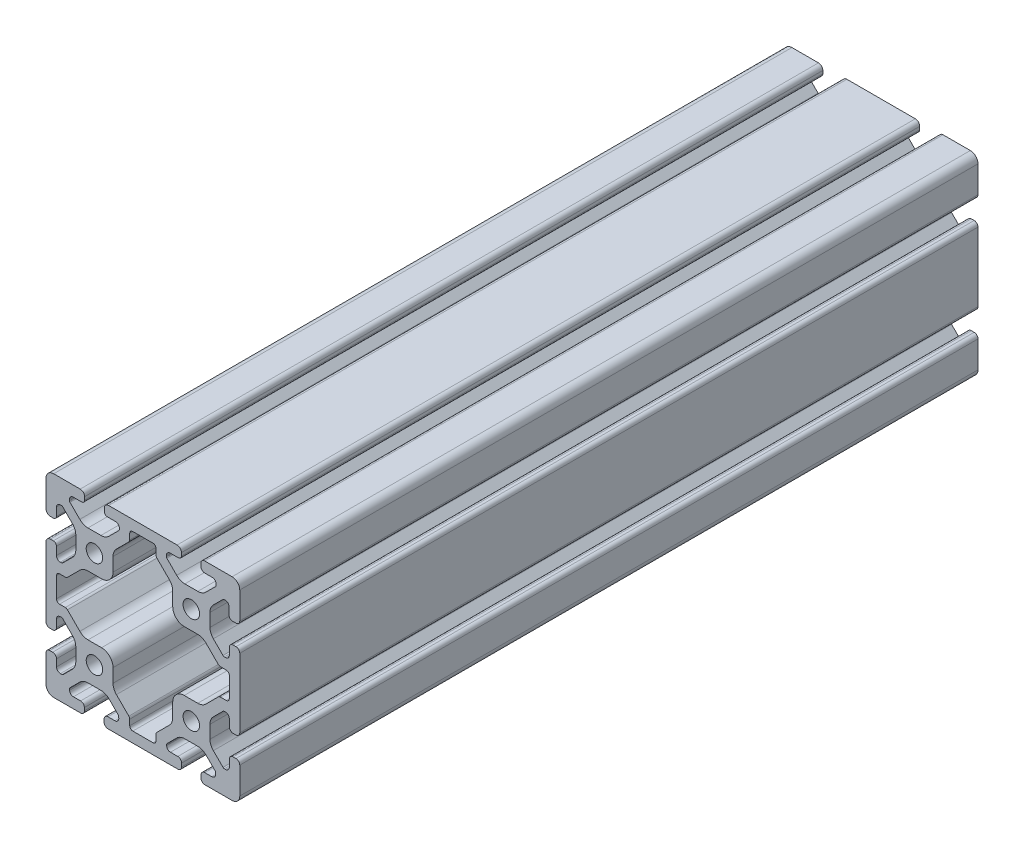
SolidWorks part; units mm, degrees
material "6061 Alloy"
ref_plane "Front Plane" through (0, 0, 0) normal (0, 0, 1) x (1, 0, 0)
ref_plane "Top Plane" through (0, 0, 0) normal (0, 1, 0) x (1, 0, 0)
ref_plane "Right Plane" through (0, 0, 0) normal (1, 0, 0) x (0, 0, -1)
sketch "Sketch1" plane through (0, 0, 0) normal (0, 0, 1) x (1, 0, 0)
  line L0 (0, -40) -> (0, 40) construction
  line L1 (0, 0) -> (-43.5804, 43.5804) construction
  line L2 (-20, 20) -> (-47.7323, 20) construction
  line L3 (-20, 20) -> (3.796, 43.796) construction
  line L4 (-20, 20) -> (-20, 43.5758) construction
  line L5 (-20, -27.7) -> (-20, -47.5576) construction
  line L131 (29.0912, 26.0365) -> (33.0827, 30.028)
  line L132 (27.7, 17.3222) -> (27.7, 22.6778)
  line L133 (29.0912, 13.9635) -> (33.0827, 9.972)
  line L134 (33.6201, 9.7494) -> (34.11, 9.7494)
  line L135 (35.68, 11.3194) -> (35.68, 14.2221)
  line L136 (37.25, 15.7921) -> (38.43, 15.7921)
  line L137 (40, 14.2221) -> (40, 7.0214)
  line L138 (40, 7.0214) -> (40, -7.0214)
  line L139 (40, -7.0214) -> (40, -14.2221)
  line L140 (38.43, -15.7921) -> (37.25, -15.7921)
  line L141 (35.68, -14.2221) -> (35.68, -11.3194)
  line L142 (33.6201, -9.7494) -> (34.11, -9.7494)
  line L143 (29.0912, -13.9635) -> (33.0827, -9.972)
  line L144 (27.7, -22.6778) -> (27.7, -17.3222)
  line L145 (29.0912, -26.0365) -> (33.0827, -30.028)
  line L146 (33.6201, -30.2506) -> (34.11, -30.2506)
  line L147 (35.68, -28.6806) -> (35.68, -25.7779)
  line L148 (37.25, -24.2079) -> (38.43, -24.2079)
  line L149 (40, -25.7779) -> (40, -33.0259)
  line L150 (40, -33.0259) -> (40, -36.83)
  line L151 (36.83, -40) -> (32.9998, -40)
  line L152 (32.9998, -40) -> (25.5696, -40)
  line L153 (23.9996, -38.43) -> (23.9996, -37.25)
  line L154 (25.5696, -35.68) -> (28.4723, -35.68)
  line L155 (30.0413, -34.0552) -> (30.0171, -33.3605)
  line L156 (29.7949, -32.8496) -> (26.0365, -29.0912)
  line L157 (17.3222, -27.7) -> (22.6778, -27.7)
  line L158 (10.035, -33.0197) -> (13.9635, -29.0912)
  line L159 (9.8124, -33.8926) -> (9.8124, -33.5571)
  line L160 (11.3824, -35.4626) -> (14.4246, -35.4626)
  line L161 (15.9946, -37.0326) -> (15.9946, -38.43)
  line L162 (14.4246, -40) -> (6.9987, -40)
  line L163 (6.9987, -40) -> (-6.9987, -40)
  line L164 (-6.9987, -40) -> (-14.4292, -40)
  line L165 (-15.9992, -38.43) -> (-15.9992, -37.25)
  line L166 (-14.4292, -35.68) -> (-11.5265, -35.68)
  line L167 (-9.9574, -34.0552) -> (-9.9816, -33.3618)
  line L168 (-10.2038, -32.8509) -> (-13.9635, -29.0912)
  line L169 (-22.6778, -27.7) -> (-17.3222, -27.7)
  line L170 (-30.028, -33.0827) -> (-26.0365, -29.0912)
  line L171 (-30.2506, -34.11) -> (-30.2506, -33.6201)
  line L172 (-28.6806, -35.68) -> (-25.7231, -35.68)
  line L173 (-24.1531, -37.25) -> (-24.1531, -38.43)
  line L174 (-25.7231, -40) -> (-33, -40)
  line L175 (-33, -40) -> (-36.83, -40)
  line L176 (-40, -36.83) -> (-40, -33.0191)
  line L177 (-40, -33.0191) -> (-40, -25.591)
  line L178 (-38.43, -24.021) -> (-37.25, -24.021)
  line L179 (-35.68, -28.4937) -> (-35.68, -25.591)
  line L180 (-34.0552, -30.0627) -> (-33.3827, -30.0392)
  line L181 (-32.8718, -29.8171) -> (-29.0912, -26.0365)
  line L182 (-27.7, -22.6778) -> (-27.7, -17.3222)
  line L183 (-29.0912, -13.9635) -> (-33.0827, -9.972)
  line L184 (-34.11, -9.7494) -> (-33.6201, -9.7494)
  line L185 (-35.68, -11.3194) -> (-35.68, -14.4473)
  line L186 (-38.43, -16.0173) -> (-37.25, -16.0173)
  line L187 (-40, -14.4473) -> (-40, -7.0169)
  line L188 (-40, -7.0169) -> (-40, 7.0169)
  line L189 (-40, 7.0169) -> (-40, 14.1348)
  line L190 (-38.1948, 15.94) -> (-36.9772, 15.94)
  line L191 (-35.68, 11.3194) -> (-35.68, 14.6428)
  line L192 (-34.11, 9.7494) -> (-33.6201, 9.7494)
  line L193 (-33.0827, 9.972) -> (-29.0912, 13.9635)
  line L194 (-27.7, 17.3222) -> (-27.7, 22.6778)
  line L195 (-29.0912, 26.0365) -> (-33.0827, 30.028)
  line L196 (-34.11, 30.2506) -> (-33.6201, 30.2506)
  line L197 (-35.68, 28.6806) -> (-35.68, 25.3572)
  line L198 (-38.1948, 24.06) -> (-36.9772, 24.06)
  line L199 (-40, 25.8652) -> (-40, 33.3181)
  line L200 (-40, 33.3181) -> (-40, 36.83)
  line L201 (-36.83, 40) -> (-33.0314, 40)
  line L202 (-33.0314, 40) -> (-25.8652, 40)
  line L203 (-24.06, 36.9772) -> (-24.06, 38.1948)
  line L204 (-25.3572, 35.68) -> (-28.7018, 35.68)
  line L205 (-30.285, 33.6069) -> (-30.285, 34.0968)
  line L206 (-30.0961, 33.1508) -> (-26.0365, 29.0912)
  line L207 (-22.6778, 27.7) -> (-17.3222, 27.7)
  line L208 (-13.9635, 29.0912) -> (-9.9039, 33.1508)
  line L209 (-9.715, 33.6069) -> (-9.715, 34.0968)
  line L210 (-14.6428, 35.68) -> (-11.2982, 35.68)
  line L211 (-15.94, 36.9772) -> (-15.94, 38.1948)
  line L212 (-14.1348, 40) -> (-6.9844, 40)
  line L213 (-6.9844, 40) -> (6.9844, 40)
  line L214 (6.9844, 40) -> (14.1348, 40)
  line L215 (15.94, 36.9772) -> (15.94, 38.1948)
  line L216 (14.6428, 35.68) -> (11.2982, 35.68)
  line L217 (9.715, 33.6069) -> (9.715, 34.0968)
  line L218 (9.9039, 33.1508) -> (13.9635, 29.0912)
  line L219 (17.3222, 27.7) -> (22.6778, 27.7)
  line L220 (26.0365, 29.0912) -> (30.028, 33.0827)
  line L221 (30.2506, 33.6201) -> (30.2506, 34.11)
  line L222 (25.5409, 35.679) -> (28.6258, 35.679)
  line L223 (23.9709, 37.249) -> (23.9709, 38.43)
  line L224 (25.5409, 40) -> (36.83, 40)
  line L226 (40, 36.83) -> (40, 32.9339)
  line L227 (40, 32.9339) -> (40, 25.7779)
  line L228 (38.43, 24.2079) -> (37.0956, 24.2079)
  line L229 (35.5256, 25.7779) -> (35.5256, 28.6806)
  line L230 (33.6201, 30.2506) -> (33.9556, 30.2506)
  line L231 (17.07, 12.32) -> (22.6578, 12.32)
  line L232 (26.0165, 10.9288) -> (31.1439, 5.8014)
  line L233 (32.0419, 5.4294) -> (34.41, 5.4294)
  line L234 (35.68, -4.1594) -> (35.68, 4.1594)
  line L235 (32.0419, -5.4294) -> (34.41, -5.4294)
  line L236 (26.0165, -10.9288) -> (31.1439, -5.8014)
  line L237 (17.07, -12.32) -> (22.6578, -12.32)
  line L238 (12.32, -22.6578) -> (12.32, -17.07)
  line L239 (5.8014, -31.1439) -> (10.9288, -26.0165)
  line L240 (5.4294, -34.41) -> (5.4294, -32.0419)
  line L241 (-4.1594, -35.68) -> (4.1594, -35.68)
  line L242 (-5.4294, -34.41) -> (-5.4294, -32.0419)
  line L243 (-5.8014, -31.1439) -> (-10.9288, -26.0165)
  line L244 (-12.32, -22.6578) -> (-12.32, -17.07)
  line L245 (-22.6578, -12.32) -> (-17.07, -12.32)
  line L246 (-26.0165, -10.9288) -> (-31.1439, -5.8014)
  line L247 (-34.41, -5.4294) -> (-32.0419, -5.4294)
  line L248 (-35.68, -4.1594) -> (-35.68, 4.1594)
  line L249 (-34.41, 5.4294) -> (-32.0419, 5.4294)
  line L250 (-31.1439, 5.8014) -> (-26.0165, 10.9288)
  line L251 (-22.6578, 12.32) -> (-17.07, 12.32)
  line L252 (-12.32, 17.07) -> (-12.32, 22.6578)
  line L253 (-10.9288, 26.0165) -> (-5.8014, 31.1439)
  line L254 (-5.4294, 32.0419) -> (-5.4294, 34.41)
  line L255 (-4.1594, 35.68) -> (4.1594, 35.68)
  line L256 (5.4294, 32.0419) -> (5.4294, 34.41)
  line L257 (5.8014, 31.1439) -> (10.9288, 26.0165)
  line L258 (12.32, 17.07) -> (12.32, 22.6578)
  line L260 (-40, 0) -> (40, 0) construction
  circle A116 centre (-20, 20) radius 3.4
  circle A117 centre (20, 20) radius 3.4
  circle A118 centre (20, -20) radius 3.4
  circle A119 centre (-20, -20) radius 3.4
  arc A120 (29.0912, 26.0365) -> (27.7, 22.6778) centre (32.45, 22.6778) ccw
  arc A121 (27.7, 17.3222) -> (29.0912, 13.9635) centre (32.45, 17.3222) ccw
  arc A122 (33.0827, 9.972) -> (33.6201, 9.7494) centre (33.6201, 10.5094) ccw
  arc A123 (34.11, 9.7494) -> (35.68, 11.3194) centre (34.11, 11.3194) ccw
  arc A124 (37.25, 15.7921) -> (35.68, 14.2221) centre (37.25, 14.2221) ccw
  arc A125 (40, 14.2221) -> (38.43, 15.7921) centre (38.43, 14.2221) ccw
  arc A126 (38.43, -15.7921) -> (40, -14.2221) centre (38.43, -14.2221) ccw
  arc A127 (35.68, -14.2221) -> (37.25, -15.7921) centre (37.25, -14.2221) ccw
  arc A128 (35.68, -11.3194) -> (34.11, -9.7494) centre (34.11, -11.3194) ccw
  arc A129 (33.6201, -9.7494) -> (33.0827, -9.972) centre (33.6201, -10.5094) ccw
  arc A130 (29.0912, -13.9635) -> (27.7, -17.3222) centre (32.45, -17.3222) ccw
  arc A131 (27.7, -22.6778) -> (29.0912, -26.0365) centre (32.45, -22.6778) ccw
  arc A132 (33.0827, -30.028) -> (33.6201, -30.2506) centre (33.6201, -29.4906) ccw
  arc A133 (34.11, -30.2506) -> (35.68, -28.6806) centre (34.11, -28.6806) ccw
  arc A134 (37.25, -24.2079) -> (35.68, -25.7779) centre (37.25, -25.7779) ccw
  arc A135 (40, -25.7779) -> (38.43, -24.2079) centre (38.43, -25.7779) ccw
  arc A136 (36.83, -40) -> (40, -36.83) centre (36.83, -36.83) ccw
  arc A137 (23.9996, -38.43) -> (25.5696, -40) centre (25.5696, -38.43) ccw
  arc A138 (25.5696, -35.68) -> (23.9996, -37.25) centre (25.5696, -37.25) ccw
  arc A139 (28.4723, -35.68) -> (30.0413, -34.0552) centre (28.4723, -34.11) ccw
  arc A140 (30.0171, -33.3605) -> (29.7949, -32.8496) centre (29.2575, -33.387) ccw
  arc A141 (26.0365, -29.0912) -> (22.6778, -27.7) centre (22.6778, -32.45) ccw
  arc A142 (17.3222, -27.7) -> (13.9635, -29.0912) centre (17.3222, -32.45) ccw
  arc A143 (10.035, -33.0197) -> (9.8124, -33.5571) centre (10.5724, -33.5571) ccw
  arc A144 (9.8124, -33.8926) -> (11.3824, -35.4626) centre (11.3824, -33.8926) ccw
  arc A145 (15.9946, -37.0326) -> (14.4246, -35.4626) centre (14.4246, -37.0326) ccw
  arc A146 (14.4246, -40) -> (15.9946, -38.43) centre (14.4246, -38.43) ccw
  arc A147 (-15.9992, -38.43) -> (-14.4292, -40) centre (-14.4292, -38.43) ccw
  arc A148 (-14.4292, -35.68) -> (-15.9992, -37.25) centre (-14.4292, -37.25) ccw
  arc A149 (-11.5265, -35.68) -> (-9.9574, -34.0552) centre (-11.5265, -34.11) ccw
  arc A150 (-9.9816, -33.3618) -> (-10.2038, -32.8509) centre (-10.7412, -33.3883) ccw
  arc A151 (-13.9635, -29.0912) -> (-17.3222, -27.7) centre (-17.3222, -32.45) ccw
  arc A152 (-22.6778, -27.7) -> (-26.0365, -29.0912) centre (-22.6778, -32.45) ccw
  arc A153 (-30.028, -33.0827) -> (-30.2506, -33.6201) centre (-29.4906, -33.6201) ccw
  arc A154 (-30.2506, -34.11) -> (-28.6806, -35.68) centre (-28.6806, -34.11) ccw
  arc A155 (-24.1531, -37.25) -> (-25.7231, -35.68) centre (-25.7231, -37.25) ccw
  arc A156 (-25.7231, -40) -> (-24.1531, -38.43) centre (-25.7231, -38.43) ccw
  arc A157 (-40, -36.83) -> (-36.83, -40) centre (-36.83, -36.83) ccw
  arc A158 (-38.43, -24.021) -> (-40, -25.591) centre (-38.43, -25.591) ccw
  arc A159 (-35.68, -25.591) -> (-37.25, -24.021) centre (-37.25, -25.591) ccw
  arc A160 (-35.68, -28.4937) -> (-34.0552, -30.0627) centre (-34.11, -28.4937) ccw
  arc A161 (-33.3827, -30.0392) -> (-32.8718, -29.8171) centre (-33.4092, -29.2797) ccw
  arc A162 (-29.0912, -26.0365) -> (-27.7, -22.6778) centre (-32.45, -22.6778) ccw
  arc A163 (-27.7, -17.3222) -> (-29.0912, -13.9635) centre (-32.45, -17.3222) ccw
  arc A164 (-33.0827, -9.972) -> (-33.6201, -9.7494) centre (-33.6201, -10.5094) ccw
  arc A165 (-34.11, -9.7494) -> (-35.68, -11.3194) centre (-34.11, -11.3194) ccw
  arc A166 (-37.25, -16.0173) -> (-35.68, -14.4473) centre (-37.25, -14.4473) ccw
  arc A167 (-40, -14.4473) -> (-38.43, -16.0173) centre (-38.43, -14.4473) ccw
  arc A168 (-38.1948, 15.94) -> (-40, 14.1348) centre (-38.1948, 14.1348) ccw
  arc A169 (-35.68, 14.6428) -> (-36.9772, 15.94) centre (-36.9772, 14.6428) ccw
  arc A170 (-35.68, 11.3194) -> (-34.11, 9.7494) centre (-34.11, 11.3194) ccw
  arc A171 (-33.6201, 9.7494) -> (-33.0827, 9.972) centre (-33.6201, 10.5094) ccw
  arc A172 (-29.0912, 13.9635) -> (-27.7, 17.3222) centre (-32.45, 17.3222) ccw
  arc A173 (-27.7, 22.6778) -> (-29.0912, 26.0365) centre (-32.45, 22.6778) ccw
  arc A174 (-33.0827, 30.028) -> (-33.6201, 30.2506) centre (-33.6201, 29.4906) ccw
  arc A175 (-34.11, 30.2506) -> (-35.68, 28.6806) centre (-34.11, 28.6806) ccw
  arc A176 (-36.9772, 24.06) -> (-35.68, 25.3572) centre (-36.9772, 25.3572) ccw
  arc A177 (-40, 25.8652) -> (-38.1948, 24.06) centre (-38.1948, 25.8652) ccw
  arc A178 (-36.83, 40) -> (-40, 36.83) centre (-36.83, 36.83) ccw
  arc A179 (-24.06, 38.1948) -> (-25.8652, 40) centre (-25.8652, 38.1948) ccw
  arc A180 (-25.3572, 35.68) -> (-24.06, 36.9772) centre (-25.3572, 36.9772) ccw
  arc A181 (-28.7018, 35.68) -> (-30.285, 34.0968) centre (-28.7018, 34.0968) ccw
  arc A182 (-30.285, 33.6069) -> (-30.0961, 33.1508) centre (-29.6399, 33.6069) ccw
  arc A183 (-26.0365, 29.0912) -> (-22.6778, 27.7) centre (-22.6778, 32.45) ccw
  arc A184 (-17.3222, 27.7) -> (-13.9635, 29.0912) centre (-17.3222, 32.45) ccw
  arc A185 (-9.9039, 33.1508) -> (-9.715, 33.6069) centre (-10.3601, 33.6069) ccw
  arc A186 (-9.715, 34.0968) -> (-11.2982, 35.68) centre (-11.2982, 34.0968) ccw
  arc A187 (-15.94, 36.9772) -> (-14.6428, 35.68) centre (-14.6428, 36.9772) ccw
  arc A188 (-14.1348, 40) -> (-15.94, 38.1948) centre (-14.1348, 38.1948) ccw
  arc A189 (15.94, 38.1948) -> (14.1348, 40) centre (14.1348, 38.1948) ccw
  arc A190 (14.6428, 35.68) -> (15.94, 36.9772) centre (14.6428, 36.9772) ccw
  arc A191 (11.2982, 35.68) -> (9.715, 34.0968) centre (11.2982, 34.0968) ccw
  arc A192 (9.715, 33.6069) -> (9.9039, 33.1508) centre (10.3601, 33.6069) ccw
  arc A193 (13.9635, 29.0912) -> (17.3222, 27.7) centre (17.3222, 32.45) ccw
  arc A194 (22.6778, 27.7) -> (26.0365, 29.0912) centre (22.6778, 32.45) ccw
  arc A195 (30.028, 33.0827) -> (30.2506, 33.6201) centre (29.4906, 33.6201) ccw
  arc A196 (30.2506, 34.11) -> (28.6258, 35.679) centre (28.6806, 34.11) ccw
  arc A197 (23.9709, 37.249) -> (25.5409, 35.679) centre (25.5409, 37.249) ccw
  arc A198 (25.5409, 40) -> (23.9709, 38.43) centre (25.5409, 38.43) ccw
  arc A199 (40, 36.83) -> (36.83, 40) centre (36.83, 36.83) ccw
  arc A200 (38.43, 24.2079) -> (40, 25.7779) centre (38.43, 25.7779) ccw
  arc A201 (35.5256, 25.7779) -> (37.0956, 24.2079) centre (37.0956, 25.7779) ccw
  arc A202 (35.5256, 28.6806) -> (33.9556, 30.2506) centre (33.9556, 28.6806) ccw
  arc A203 (33.6201, 30.2506) -> (33.0827, 30.028) centre (33.6201, 29.4906) ccw
  arc A204 (26.0165, 10.9288) -> (22.6578, 12.32) centre (22.6578, 7.57) ccw
  arc A205 (31.1439, 5.8014) -> (32.0419, 5.4294) centre (32.0419, 6.6994) ccw
  arc A206 (35.68, 4.1594) -> (34.41, 5.4294) centre (34.41, 4.1594) ccw
  arc A207 (34.41, -5.4294) -> (35.68, -4.1594) centre (34.41, -4.1594) ccw
  arc A208 (32.0419, -5.4294) -> (31.1439, -5.8014) centre (32.0419, -6.6994) ccw
  arc A209 (22.6578, -12.32) -> (26.0165, -10.9288) centre (22.6578, -7.57) ccw
  arc A210 (17.07, -12.32) -> (12.32, -17.07) centre (17.07, -17.07) ccw
  arc A211 (10.9288, -26.0165) -> (12.32, -22.6578) centre (7.57, -22.6578) ccw
  arc A212 (5.8014, -31.1439) -> (5.4294, -32.0419) centre (6.6994, -32.0419) ccw
  arc A213 (4.1594, -35.68) -> (5.4294, -34.41) centre (4.1594, -34.41) ccw
  arc A214 (-5.4294, -34.41) -> (-4.1594, -35.68) centre (-4.1594, -34.41) ccw
  arc A215 (-5.4294, -32.0419) -> (-5.8014, -31.1439) centre (-6.6994, -32.0419) ccw
  arc A216 (-12.32, -22.6578) -> (-10.9288, -26.0165) centre (-7.57, -22.6578) ccw
  arc A217 (-12.32, -17.07) -> (-17.07, -12.32) centre (-17.07, -17.07) ccw
  arc A218 (-26.0165, -10.9288) -> (-22.6578, -12.32) centre (-22.6578, -7.57) ccw
  arc A219 (-31.1439, -5.8014) -> (-32.0419, -5.4294) centre (-32.0419, -6.6994) ccw
  arc A220 (-35.68, -4.1594) -> (-34.41, -5.4294) centre (-34.41, -4.1594) ccw
  arc A221 (-34.41, 5.4294) -> (-35.68, 4.1594) centre (-34.41, 4.1594) ccw
  arc A222 (-32.0419, 5.4294) -> (-31.1439, 5.8014) centre (-32.0419, 6.6994) ccw
  arc A223 (-22.6578, 12.32) -> (-26.0165, 10.9288) centre (-22.6578, 7.57) ccw
  arc A224 (-17.07, 12.32) -> (-12.32, 17.07) centre (-17.07, 17.07) ccw
  arc A225 (-10.9288, 26.0165) -> (-12.32, 22.6578) centre (-7.57, 22.6578) ccw
  arc A226 (-5.8014, 31.1439) -> (-5.4294, 32.0419) centre (-6.6994, 32.0419) ccw
  arc A227 (-4.1594, 35.68) -> (-5.4294, 34.41) centre (-4.1594, 34.41) ccw
  arc A228 (5.4294, 34.41) -> (4.1594, 35.68) centre (4.1594, 34.41) ccw
  arc A229 (5.4294, 32.0419) -> (5.8014, 31.1439) centre (6.6994, 32.0419) ccw
  arc A230 (12.32, 22.6578) -> (10.9288, 26.0165) centre (7.57, 22.6578) ccw
  arc A231 (12.32, 17.07) -> (17.07, 12.32) centre (17.07, 17.07) ccw
  dimension "D8" = 6.8
  dimension "D1" = 80
  dimension "D2" = 40
  dimension "D3" = 20
  dimension "D4" = 20.57
  dimension "D5" = 4.32
  dimension "D6" = 4.32
  dimension "D7" = 8.12
  dimension "D9" = 4.32
  dimension "D10" = 12.3
extrude "Extrude1" add sketch "Sketch1" against normal blind 304.8
